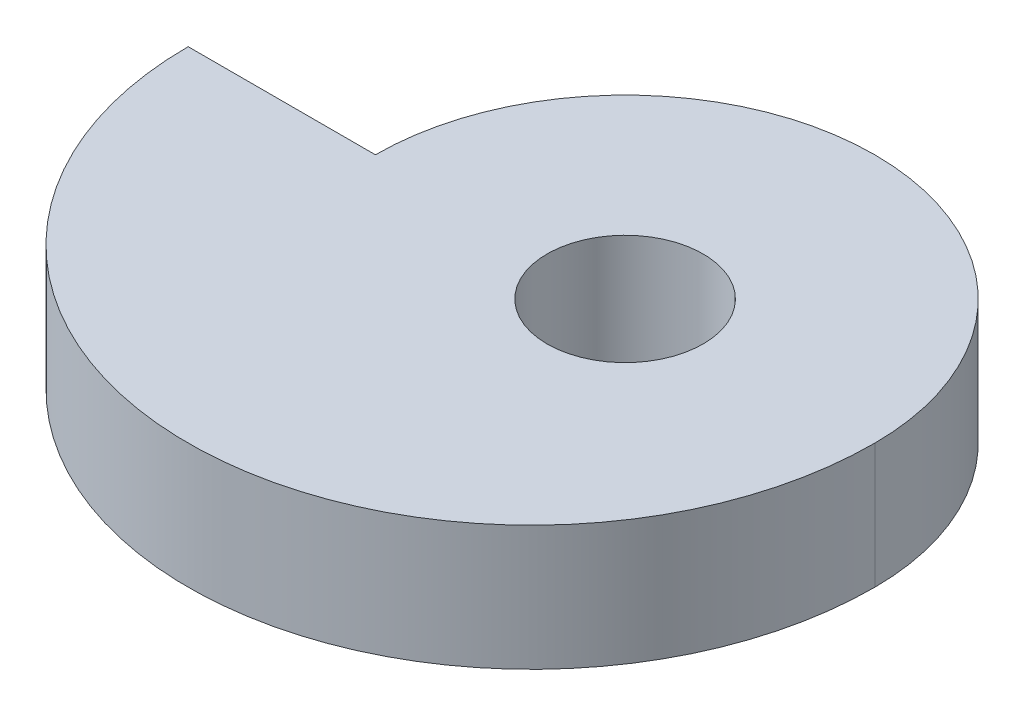
SolidWorks part; units mm, degrees
ref_plane "Front Plane" through (0, 0, 0) normal (0, 0, 1) x (1, 0, 0)
ref_plane "Top Plane" through (0, 0, 0) normal (0, 1, 0) x (1, 0, 0)
ref_plane "Right Plane" through (0, 0, 0) normal (1, 0, 0) x (0, 0, -1)
sketch "Sketch1" plane through (0, 0, 0) normal (0, 1, 0) x (1, 0, 0)
  line L0 (-8.89, 0) -> (-5.08, 0)
  circle A0 centre (0, 0) radius 1.5875
  arc A1 (5.08, 0) -> (-5.08, 0) centre (0, 0) ccw
  arc A2 (5.08, 0) -> (-8.89, 0) centre (-1.905, 0) cw
  dimension "D1" = 3.175
  dimension "D2" = 10.16
  dimension "D3" = 3.81
extrude "Boss-Extrude1" add sketch "Sketch1" along normal blind 2.54
